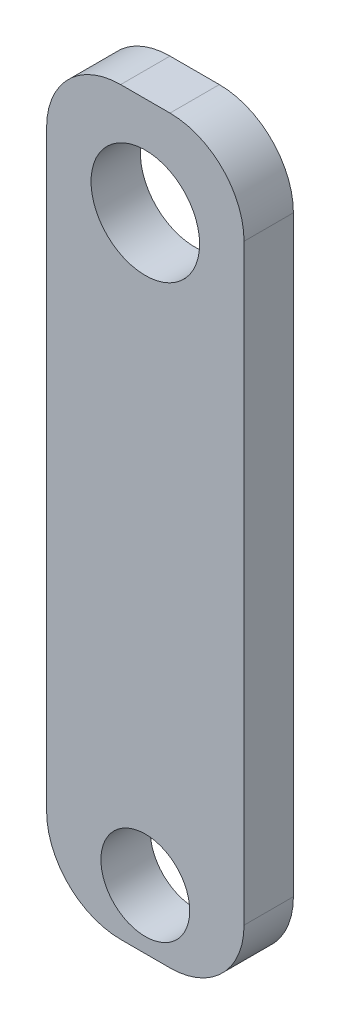
SolidWorks part; units mm, degrees
material "Kiefer"
ref_plane "Ebene vorne" through (0, 0, 0) normal (0, 0, 1) x (1, 0, 0)
ref_plane "Ebene oben" through (0, 0, 0) normal (0, 1, 0) x (1, 0, 0)
ref_plane "Ebene rechts" through (0, 0, 0) normal (1, 0, 0) x (0, 0, -1)
sketch "Skizze1" plane through (0, 0, 0) normal (0, 1, 0) x (1, 0, 0)
  line L1 (-20, 5) -> (20, 5)
  line L2 (-20, 5) -> (-20, -5)
  line L3 (-20, -5) -> (20, -5)
  line L4 (20, 5) -> (20, -5)
  line L5 (-20, 5) -> (20, -5) construction
  line L6 (-20, -5) -> (20, 5) construction
  point P0 (0, 0)
  dimension "D1" = 40
  dimension "D2" = 10
extrude "Aufsatz-Linear austragen1" add sketch "Skizze1" along normal blind 150
sketch "Skizze2" plane through (0, 0, 5) normal (0, 0, 1) x (1, 0, 0)
  line L0 (20, 150) -> (20, 0) construction
  line L1 (-20, 150) -> (20, 150) construction
  line L2 (-20, 150) -> (-20, 110) construction
  line L3 (-20, 110) -> (20, 110) construction
  line L4 (20, 150) -> (20, 110) construction
  line L5 (-20, 110) -> (20, 150) construction
  line L6 (20, 150) -> (-20, 150) construction
  line L7 (-20, 150) -> (20, 110) construction
  circle A0 centre (0, 130) radius 11
  dimension "D1" = 22
extrude "Schnitt-Linear austragen1" cut sketch "Skizze2" against normal through all
sketch "Skizze3" plane through (0, 0, 5) normal (0, 0, 1) x (1, 0, 0)
  line L0 (0, 0) -> (0, 12) construction
  circle A0 centre (0, 12) radius 9
  dimension "D1" = 12
  dimension "D2" = 18
extrude "Schnitt-Linear austragen5" cut sketch "Skizze3" against normal through all
fillet "Verrundung1" radius 15 4 edges at (-20, 0, 0) (20, 0, 0) (-20, 150, 0) (20, 150, 0)
